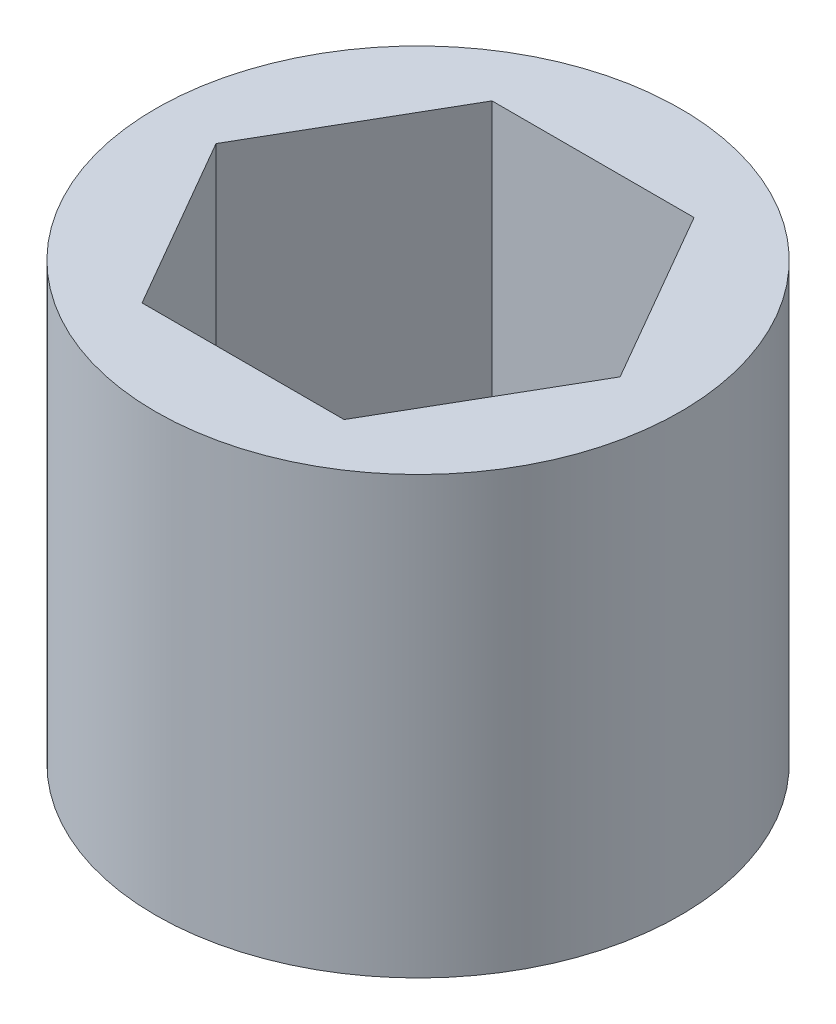
SolidWorks part; units mm, degrees
material "PET"
ref_plane "Front Plane" through (0, 0, 0) normal (0, 0, 1) x (1, 0, 0)
ref_plane "Top Plane" through (0, 0, 0) normal (0, 1, 0) x (1, 0, 0)
ref_plane "Right Plane" through (0, 0, 0) normal (1, 0, 0) x (0, 0, -1)
sketch "Sketch1" plane through (0, 0, 0) normal (0, 1, 0) x (1, 0, 0)
  line L1 (7.3323, 0) -> (3.6662, 6.35)
  line L2 (3.6662, 6.35) -> (-3.6662, 6.35)
  line L3 (-3.6662, 6.35) -> (-7.3323, 0)
  line L4 (-7.3323, 0) -> (-3.6662, -6.35)
  line L5 (-3.6662, -6.35) -> (3.6662, -6.35)
  line L6 (3.6662, -6.35) -> (7.3323, 0)
  circle A0 centre (0, 0) radius 6.35 construction
  circle A1 centre (0, 0) radius 9.525
  dimension "D1" = 19.05
  dimension "D2" = 12.7
extrude "Boss-Extrude1" add sketch "Sketch1" along normal blind 15.8242
